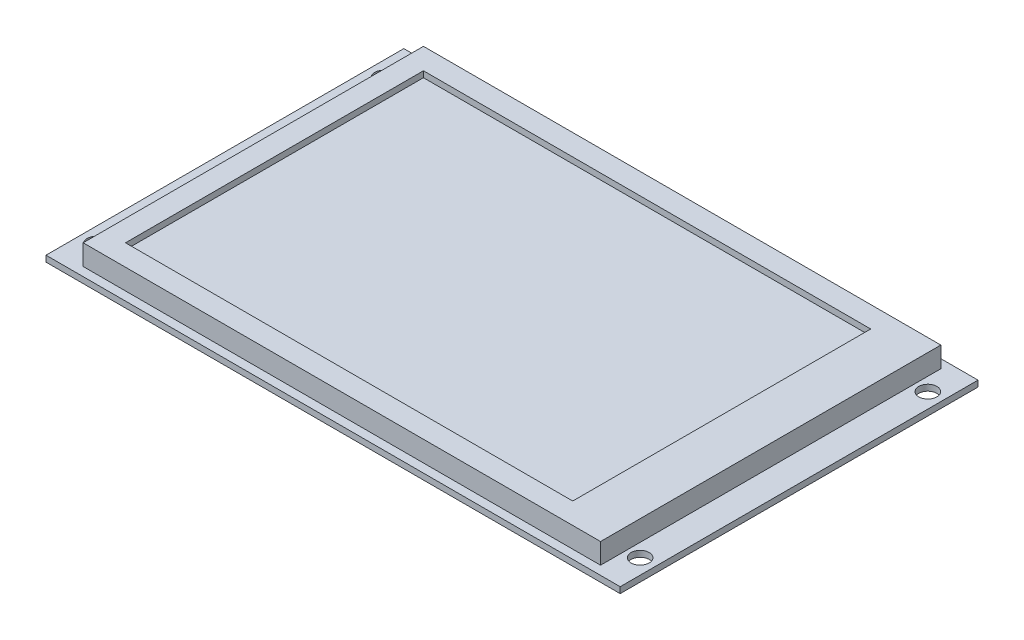
SolidWorks part; units mm, degrees
ref_plane "Alzado" through (0, 0, 0) normal (0, 0, 1) x (1, 0, 0)
ref_plane "Planta" through (0, 0, 0) normal (0, 1, 0) x (1, 0, 0)
ref_plane "Vista lateral" through (0, 0, 0) normal (1, 0, 0) x (0, 0, -1)
sketch "Croquis1" plane through (0, 0, 0) normal (0, 1, 0) x (1, 0, 0)
  line L1 (47.5, 29.6) -> (-47.5, 29.6)
  line L2 (47.5, 29.6) -> (47.5, -29.6)
  line L3 (47.5, -29.6) -> (-47.5, -29.6)
  line L4 (-47.5, 29.6) -> (-47.5, -29.6)
  line L5 (47.5, 29.6) -> (-47.5, -29.6) construction
  line L6 (47.5, -29.6) -> (-47.5, 29.6) construction
  point P0 (0, 0)
  dimension "D1" = 95
  dimension "D2" = 59.2
extrude "Saliente-Extruir1" add sketch "Croquis1" along normal blind 1
sketch "Croquis2" plane through (0, 1, 0) normal (0, 1, 0) x (1, 0, 0)
  line L1 (42.8, 28.15) -> (-42.8, 28.15)
  line L2 (42.8, 28.15) -> (42.8, -28.15)
  line L3 (42.8, -28.15) -> (-42.8, -28.15)
  line L4 (-42.8, 28.15) -> (-42.8, -28.15)
  line L5 (42.8, 28.15) -> (-42.8, -28.15) construction
  line L6 (42.8, -28.15) -> (-42.8, 28.15) construction
  point P0 (0, 0)
  dimension "D1" = 85.6
  dimension "D2" = 56.3
extrude "Saliente-Extruir2" add sketch "Croquis2" along normal blind 3.4
sketch "Croquis3" plane through (0, 4.4, 0) normal (0, 1, 0) x (1, 0, 0)
  line L0 (-42.8, 28.15) -> (-42.8, -28.15) construction
  line L1 (-39.3, 24.65) -> (34.7, 24.65)
  line L2 (-39.3, 24.65) -> (-39.3, -24.65)
  line L3 (-39.3, -24.65) -> (34.7, -24.65)
  line L4 (34.7, 24.65) -> (34.7, -24.65)
  line L5 (-42.8, -28.15) -> (42.8, -28.15) construction
  line L6 (42.8, 28.15) -> (-42.8, 28.15) construction
  dimension "D1" = 74
  dimension "D2" = 3.5
  dimension "D3" = 3.5
  dimension "D4" = 3.5
extrude "Cortar-Extruir1" cut sketch "Croquis3" against normal blind 1
sketch "Croquis4" plane through (0, 1, 0) normal (0, 1, 0) x (1, 0, 0)
  line L0 (0, 0) -> (0, 24.65) construction
  line L1 (34.7, 24.65) -> (-39.3, 24.65) construction
  line L2 (0, 0) -> (34.7, 0) construction
  line L3 (34.7, -24.65) -> (34.7, 24.65) construction
  line L4 (45, -23.8) -> (46.5, -23.8) construction
  line L5 (47.5, -29.6) -> (47.5, 29.6) construction
  line L6 (45, -23.8) -> (45, -25.3) construction
  line L7 (-47.5, -29.6) -> (47.5, -29.6) construction
  circle A0 centre (45, -23.8) radius 1.5
  circle A1 centre (45, 23.8) radius 1.5
  circle A2 centre (-45, -23.8) radius 1.5
  circle A3 centre (-45, 23.8) radius 1.5
  dimension "D1" = 3
  dimension "D2" = 1
  dimension "D3" = 4.3
extrude "Cortar-Extruir2" cut sketch "Croquis4" against normal blind 11
sketch "Croquis5" plane through (0, 1, 0) normal (0, 1, 0) x (1, 0, 0)
  circle A0 centre (-45.35, -9.63) radius 0.5
  circle A9 centre (-45.35, -7.09) radius 0.5
  circle A10 centre (-45.35, -4.55) radius 0.5
  circle A11 centre (-45.35, -2.01) radius 0.5
  circle A12 centre (-45.35, 0.53) radius 0.5
  circle A13 centre (-45.35, 3.07) radius 0.5
  circle A14 centre (-45.35, 5.61) radius 0.5
  circle A15 centre (-45.35, 8.15) radius 0.5
  circle A16 centre (-45.35, 10.69) radius 0.5
  dimension "D1" = 1
  dimension "D2" = 9
  dimension "D3" = 20.32
extrude "Cortar-Extruir3" cut sketch "Croquis5" against normal blind 10
